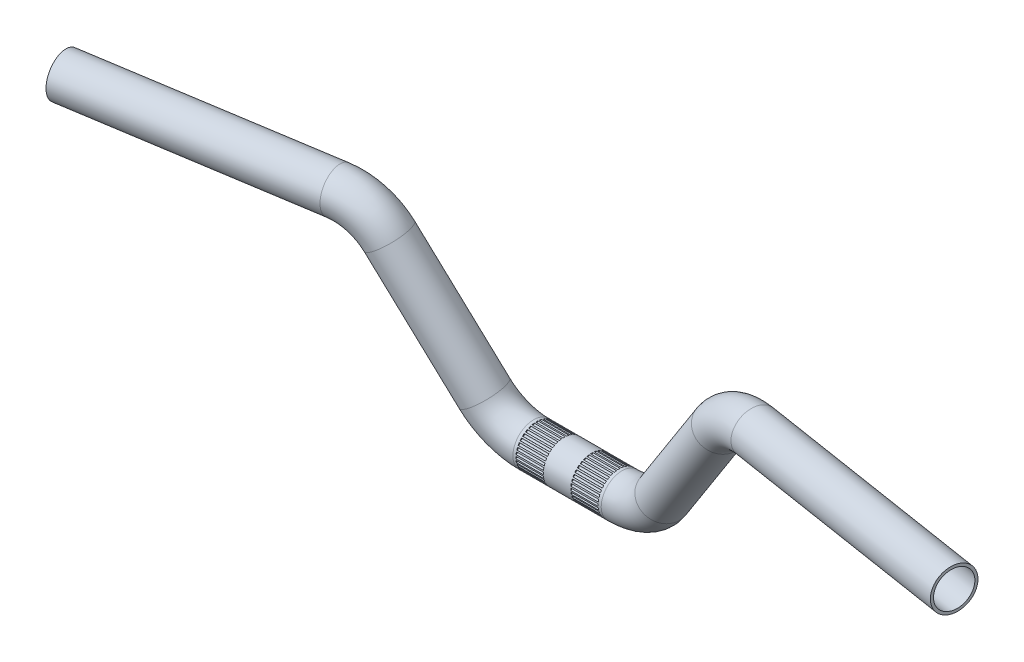
SolidWorks part; units mm, degrees
ref_plane "Front Plane" through (0, 0, 0) normal (0, 0, 1) x (1, 0, 0)
ref_plane "Top Plane" through (0, 0, 0) normal (0, 1, 0) x (1, 0, 0)
ref_plane "Right Plane" through (0, 0, 0) normal (1, 0, 0) x (0, 0, -1)
ref_plane "Plane1" through (0, 0, 25) normal (0, 0, 1) x (1, 0, 0)
ref_plane "Plane2" through (0, 0, 63) normal (0, 0, 1) x (1, 0, 0)
sketch "Sketch1" plane through (0, 0, 25) normal (0, 0, 1) x (1, 0, 0)
  point P0 (165, 140)
  dimension "D1" = 165
  dimension "140" = 140
sketch "Sketch2" plane through (0, 0, 63) normal (0, 0, 1) x (1, 0, 0)
  point P0 (406, 140)
  dimension "D1" = 406
  dimension "140" = 140
sketch3d "3DSketch1"
  line L0 (0, 0, 0) -> (40.2572, 0, 0)
  line L1 (81.3527, 21.184, 3.7828) -> (150.4303, 119.3046, 21.3044)
  line L2 (190.2658, 140, 28.9838) -> (406, 140, 63)
  arc A0 (190.2658, 140, 28.9838) -> (150.4303, 119.3046, 21.3044) centre (190.7844, 90.111, 25.6948) ccw
  arc A1 (81.3527, 21.184, 3.7828) -> (40.2572, 0, 0) centre (40.2572, 49.2214, 8.7895) ccw
  point P9 (165, 140, 25)
  point P10 (183.0141, 86.7813, 74.975)
  point P13 (66.439, 0, 0)
  point P14 (40.2572, 58.0109, -40.4318)
  dimension "D1" = 50
sketch "Sketch5" plane through (0, 0, 0) normal (1, 0, 0) x (0, 0, -1)
  circle A0 centre (0, 0) radius 19
  dimension "D1" = 38
sweep "Sweep-Thin1" add profiles "Sketch5" path "3DSketch1" parameters "D1"=2.5
mirror "Mirror1" about plane through (0, 0, 0) normal (1, 0, 0) of "Sweep-Thin1"
sketch "Sketch6" plane through (0, 0, 0) normal (1, 0, 0) x (0, 0, -1)
  circle A0 centre (0, -19) radius 1
  dimension "D1" = 19
  dimension "D2" = 2
extrude "Cut-Extrude1" cut sketch "Sketch6" against normal blind 25 from offset 12.5 offset against normal yes
pattern_circular "CirPattern1" count 36 over 360 about axis through (0, 0, 0) along (1, 0, 0) of "Cut-Extrude1"
mirror "Mirror2" about plane through (0, 0, 0) normal (1, 0, 0) of "CirPattern1", "Cut-Extrude1"
